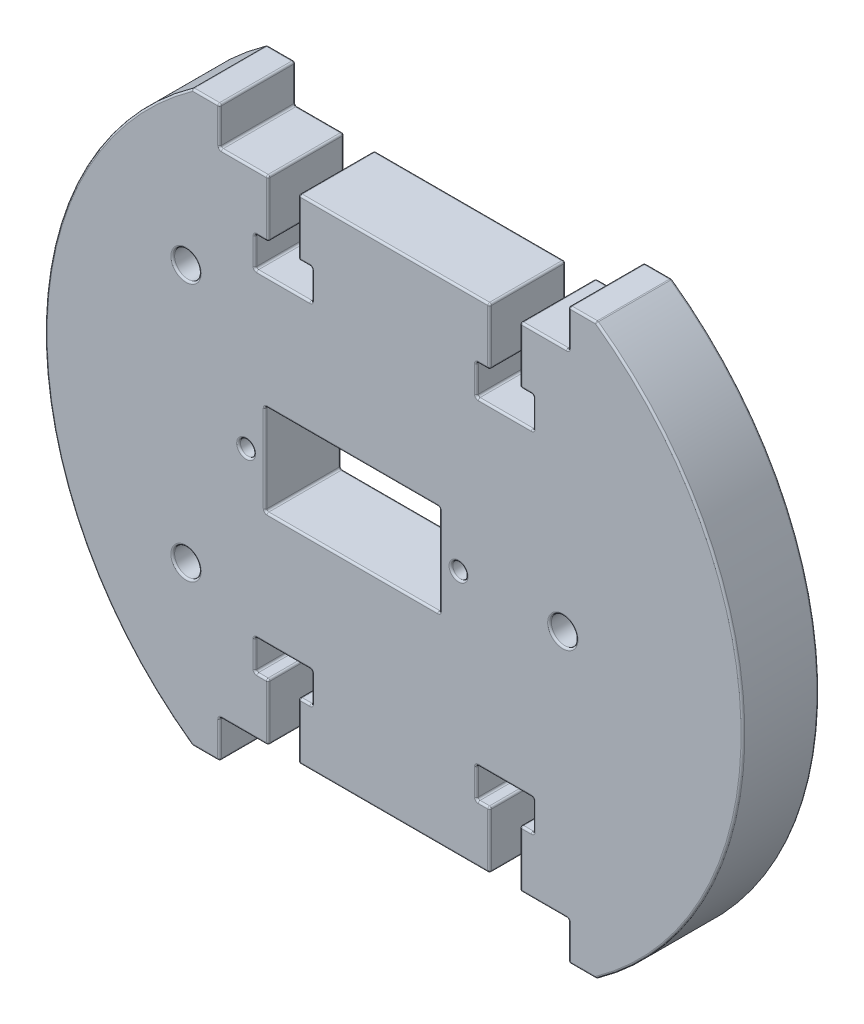
SolidWorks part; units mm, degrees
material "Cast Alloy Steel"
ref_plane "Front" through (0, 0, 0) normal (0, 0, 1) x (1, 0, 0)
ref_plane "Top" through (0, 0, 0) normal (0, 1, 0) x (1, 0, 0)
ref_plane "Right" through (0, 0, 0) normal (1, 0, 0) x (0, 0, -1)
sketch "Sketch1" plane through (0, 0, 0) normal (0, 0, 1) x (1, 0, 0)
  line L0 (26.6411, 37.5) -> (23, 37.5)
  line L1 (0, 0) -> (-46, 0) construction
  line L3 (-23, 37.5) -> (-23, 32.5)
  line L4 (-23, 32.5) -> (23, 32.5)
  line L5 (23, 37.5) -> (23, 32.5)
  line L6 (-23, 37.5) -> (-26.6411, 37.5)
  line L7 (26.6411, -37.5) -> (23, -37.5)
  line L8 (23, -37.5) -> (23, -32.5)
  line L9 (-23, -37.5) -> (-26.6411, -37.5)
  line L10 (-23, -37.5) -> (-23, -32.5)
  line L11 (-23, -32.5) -> (23, -32.5)
  line L12 (22.25, 0) -> (-5.5, 0) construction
  line L13 (6, 6) -> (-17, 6)
  line L14 (6, 6) -> (6, -6)
  line L15 (6, -6) -> (-17, -6)
  line L16 (-17, 6) -> (-17, -6)
  line L17 (6, 6) -> (-17, -6) construction
  line L18 (6, -6) -> (-17, 6) construction
  line L19 (-27.4327, 17.0005) -> (-27.4327, -17.0005) construction
  line L20 (-27.4327, 17.0005) -> (-5.5, 0) construction
  line L21 (-5.5, 0) -> (-27.4327, -17.0005) construction
  arc A0 (-26.6411, 37.5) -> (-26.6411, -37.5) centre (0, 0) ccw
  arc A1 (26.6411, -37.5) -> (26.6411, 37.5) centre (0, 0) ccw
  circle A2 centre (8.5, 0) radius 1
  circle A3 centre (-19.5, 0) radius 1
  circle A4 centre (-27.4327, -17.0005) radius 1.75
  circle A5 centre (22.25, 0) radius 1.75
  circle A6 centre (-27.4327, 17.0005) radius 1.75
  point P9 (0, 32.5)
  point P17 (-5.5, 0)
  dimension "D1" = 92
  dimension "D8" = 2
  dimension "D10" = 2
  dimension "D15" = 3.5
  dimension "D2" = 37.5
  dimension "D3" = 5
  dimension "D4" = 46
  dimension "D5" = 23
  dimension "D6" = 6
  dimension "D7" = 12
  dimension "D9" = 2.5
  dimension "D11" = 2.5
  dimension "D12" = 27.75
  dimension "D13" = 75.56
extrude "Boss-Extrude1" add sketch "Sketch1" along normal blind 10
sketch "Sketch2" plane through (0, 0, 0) normal (0, 0, -1) x (-1, 0, 0)
  line L0 (-23, 37.5) -> (-23, 32.5) construction
  line L5 (-23, 32.5) -> (23, 32.5) construction
  line L10 (-16.6, 32.5) -> (-12.6, 32.5)
  line L11 (-16.6, 32.5) -> (-16.6, 25)
  line L12 (-16.6, 25) -> (-12.6, 25)
  line L13 (-12.6, 32.5) -> (-12.6, 25)
  line L14 (-16.6, 32.5) -> (-12.6, 25) construction
  line L15 (-16.6, 25) -> (-12.6, 32.5) construction
  line L16 (0, 32.5) -> (0, 10.5726) construction
  line L17 (-18.35, 25) -> (-10.85, 25)
  line L18 (-18.35, 25) -> (-18.35, 21)
  line L19 (-18.35, 21) -> (-10.85, 21)
  line L20 (-10.85, 25) -> (-10.85, 21)
  line L21 (-18.35, 25) -> (-10.85, 21) construction
  line L22 (-18.35, 21) -> (-10.85, 25) construction
  line L23 (0, 0) -> (-30.7106, 0) construction
  line L24 (18.35, 21) -> (10.85, 25) construction
  line L25 (18.35, 25) -> (10.85, 21) construction
  line L26 (16.6, 25) -> (12.6, 32.5) construction
  line L27 (16.6, 32.5) -> (12.6, 25) construction
  line L28 (10.85, 25) -> (10.85, 21)
  line L29 (18.35, 21) -> (10.85, 21)
  line L30 (18.35, 25) -> (18.35, 21)
  line L31 (18.35, 25) -> (10.85, 25)
  line L32 (12.6, 32.5) -> (12.6, 25)
  line L33 (16.6, 25) -> (12.6, 25)
  line L34 (16.6, 32.5) -> (16.6, 25)
  line L35 (16.6, 32.5) -> (12.6, 32.5)
  line L36 (16.6, -25) -> (12.6, -32.5) construction
  line L37 (18.35, -25) -> (10.85, -21) construction
  line L38 (18.35, -21) -> (10.85, -25) construction
  line L39 (-18.35, -21) -> (-10.85, -25) construction
  line L40 (-18.35, -25) -> (-10.85, -21) construction
  line L41 (-16.6, -25) -> (-12.6, -32.5) construction
  line L42 (-16.6, -32.5) -> (-12.6, -25) construction
  line L43 (16.6, -32.5) -> (12.6, -32.5)
  line L44 (16.6, -32.5) -> (16.6, -25)
  line L45 (16.6, -25) -> (12.6, -25)
  line L46 (12.6, -32.5) -> (12.6, -25)
  line L47 (18.35, -25) -> (10.85, -25)
  line L48 (18.35, -25) -> (18.35, -21)
  line L49 (18.35, -21) -> (10.85, -21)
  line L50 (10.85, -25) -> (10.85, -21)
  line L51 (-10.85, -25) -> (-10.85, -21)
  line L52 (-18.35, -21) -> (-10.85, -21)
  line L53 (-18.35, -25) -> (-18.35, -21)
  line L54 (-18.35, -25) -> (-10.85, -25)
  line L55 (-12.6, -32.5) -> (-12.6, -25)
  line L56 (-16.6, -25) -> (-12.6, -25)
  line L57 (-16.6, -32.5) -> (-16.6, -25)
  line L58 (-16.6, -32.5) -> (-12.6, -32.5)
  point P4 (-14.6, 28.75)
  point P11 (-14.6, 23)
  point P27 (14.6, 23)
  point P28 (14.6, 28.75)
  point P45 (14.6, -28.75)
  point P46 (14.6, -23)
  point P47 (-14.6, -23)
  point P48 (-14.6, -28.75)
  line M6 (-23, -32.5) -> (23, -32.5)
  line M12 (23, 32.5) -> (-23, 32.5)
  dimension "D1" = 7.5
  dimension "D2" = 4
  dimension "D3" = 4
  dimension "D4" = 6.4
  dimension "D5" = 7.5
extrude "Cut-Extrude1" cut sketch "Sketch2" against normal through all contours L13 L11 L12 M12 | L20 L17 L12 L18 L19 | L34 L32 L31 M12 | L30 L31 L28 L29 | L57 L55 L54 M6 | L53 L54 L51 L52 | L50 L47 L45 L48 L49 | L46 L44 L45 M6
fillet "Fillet1" radius 0.25 123 edges at (-10.85, -23, 0) (-11.725, -25, 0) (-12.6, -28.75, 0) (-16.6, -28.75, 0) (-17.475, -25, 0) (-14.6, -21, 0) (-11.725, -25, 10) (-12.6, -28.75, 10) (-16.6, -28.75, 10) (-18.35, -23, 10) (-14.6, -21, 10) (-16.6, -32.5, 5) (-16.6, -25, 5) (-18.35, -25, 5) (-18.35, -21, 5) (-10.85, -21, 5) (16.6, -28.75, 0) (12.6, -28.75, 0) (11.725, -25, 0) (10.85, -23, 0) (14.6, -21, 0) (18.35, -23, 0) (17.475, -25, 0) (12.6, -28.75, 10) (11.725, -25, 10) (14.6, -21, 10) (18.35, -23, 10) (17.475, -25, 10) (16.6, -32.5, 5) (12.6, -25, 5) (10.85, -25, 5) (10.85, -21, 5) (18.35, -21, 5) (18.35, -25, 5) (16.6, -25, 5) (-12.6, 28.75, 0) (-10.85, 23, 0) (-14.6, 21, 0) (-18.35, 23, 0) (-17.475, 25, 0) (-16.6, 28.75, 10) (-11.725, 25, 10) (-10.85, 23, 10) (-14.6, 21, 10) (-17.475, 25, 10) (-12.6, 32.5, 5) (-12.6, 25, 5) (-10.85, 25, 5) (-10.85, 21, 5) (-18.35, 21, 5) (-18.35, 25, 5) (-16.6, 25, 5) (16.6, 28.75, 0) (17.475, 25, 0) (14.6, 21, 0) (11.725, 25, 0) (16.6, 28.75, 10) (17.475, 25, 10) (18.35, 23, 10) (14.6, 21, 10) (10.85, 23, 10) (12.6, 32.5, 5) (16.6, 32.5, 5) (16.6, 25, 5) (18.35, 21, 5) (10.85, 21, 5) (10.85, 25, 5) (12.6, 25, 5) (-25.6827, -17.0005, 10) (-25.6827, 17.0005, 0) (-25.6827, 17.0005, 10) (24, 0, 0) (24, 0, 10) (-18.5, 0, 10) (9.5, 0, 10) (-17, 0, 0) (-5.5, -6, 0) (6, 0, 0) (-17, 0, 10) (-5.5, -6, 10) (-5.5, 6, 10) (-17, 6, 5) (6, -6, 5) (46, 0, 0) (24.8206, 37.5, 0) (23, 35, 0) (-19.8, 32.5, 0) (0, 32.5, 0) (19.8, 32.5, 0) (-23, 35, 0) (-24.8206, 37.5, 0) (-46, 0, 0) (-24.8206, -37.5, 0) (-23, -35, 0) (0, -32.5, 0) (23, -35, 0) (24.8206, -37.5, 0) (46, 0, 10) (24.8206, 37.5, 10) (23, 35, 10) (-19.8, 32.5, 10) (0, 32.5, 10) (19.8, 32.5, 10) (-23, 35, 10) (-24.8206, -37.5, 10) (-23, -35, 10) (19.8, -32.5, 10) (0, -32.5, 10) (-19.8, -32.5, 10) (23, -35, 10) (24.8206, -37.5, 10) (26.6411, -37.5, 5) (23, -37.5, 5) (-23, -32.5, 5) (-23, -37.5, 5) (-26.6411, -37.5, 5) (-26.6411, 37.5, 5) (-23, 37.5, 5) (-23, 32.5, 5) (23, 32.5, 5) (23, 37.5, 5) (26.6411, 37.5, 5) (12.6, -32.5, 5)
